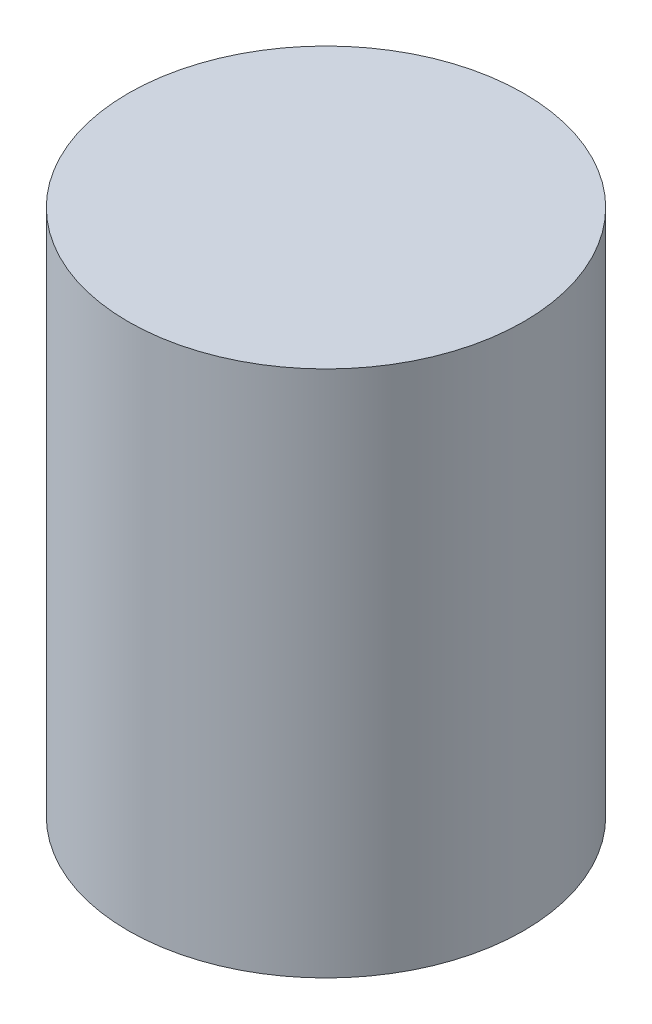
SolidWorks part; units mm, degrees
ref_plane "前视基准面" through (0, 0, 0) normal (0, 0, 1) x (1, 0, 0)
ref_plane "上视基准面" through (0, 0, 0) normal (0, 1, 0) x (1, 0, 0)
ref_plane "右视基准面" through (0, 0, 0) normal (1, 0, 0) x (0, 0, -1)
other "Configuration Table"
sketch "草图1" plane through (0, 0, 0) normal (0, 1, 0) x (1, 0, 0)
  circle A0 centre (0, 0) radius 1.5
  dimension "D1" = 3
extrude "凸台-拉伸1" add sketch "草图1" along normal blind 4
cosmetic thread "装饰螺纹线1" parameters "D2"=2
sketch "草图2" plane through (0, 0, 0) normal (0, -1, 0) x (1, 0, 0)
  line L1 (0.6944, -0.5175) -> (0.7953, 0.3427)
  line L2 (0.7953, 0.3427) -> (0.1009, 0.8601)
  line L3 (0.1009, 0.8601) -> (-0.6944, 0.5175)
  line L4 (-0.6944, 0.5175) -> (-0.7953, -0.3427)
  line L5 (-0.7953, -0.3427) -> (-0.1009, -0.8601)
  line L6 (-0.1009, -0.8601) -> (0.6944, -0.5175)
  circle A0 centre (0, 0) radius 0.75 construction
  dimension "D1" = 1.5
extrude "切除-拉伸1" cut sketch "草图2" against normal blind 2
